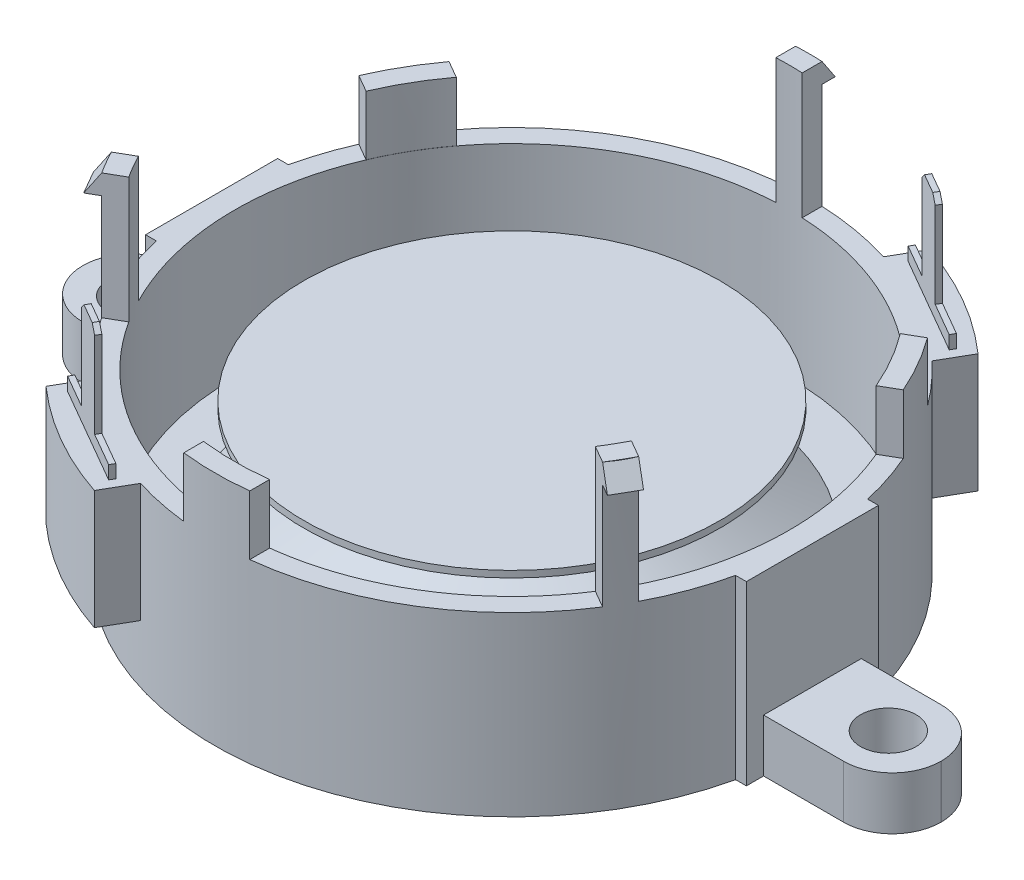
SolidWorks part; units mm, degrees
material "Полиамид ПА-6Б ТУ 6-05-988-87"
ref_plane "Спереди" through (0, 0, 0) normal (0, 0, 1) x (1, 0, 0)
ref_plane "Сверху" through (0, 0, 0) normal (0, 1, 0) x (1, 0, 0)
ref_plane "Справа" through (0, 0, 0) normal (1, 0, 0) x (0, 0, -1)
sketch "Эскиз1" plane through (0, 0, 0) normal (0, 1, 0) x (1, 0, 0)
  circle A0 centre (0, 0) radius 22.5
  dimension "D1" = 45
extrude "Бобышка-Вытянуть1" add sketch "Эскиз1" along normal blind 13.4
sketch "Эскиз2" plane through (0, 0, 0) normal (0, -1, 0) x (1, 0, 0)
  line L0 (0, 22.5) -> (0, 0) construction
  line L1 (22.1937, 3.7) -> (32.5, 3.7)
  line L3 (22.1937, -3.7) -> (32.5, -3.7)
  line L4 (32.5, 3.7) -> (32.5, -3.7)
  line L5 (-22.1937, -3.7) -> (-32.5, -3.7)
  line L7 (-22.1937, 3.7) -> (-32.5, 3.7)
  line L8 (-32.5, -3.7) -> (-32.5, 3.7)
  line L9 (32.5, 0) -> (-32.5, 0) construction
  circle A0 centre (0, 0) radius 22.5 construction
  circle A1 centre (0, 0) radius 22.5
  arc A2 (-22.1937, 3.7) -> (-22.1937, -3.7) centre (0, 0) ccw
  arc A3 (22.1937, -3.7) -> (22.1937, 3.7) centre (0, 0) ccw
  circle A4 centre (28.5, 0) radius 2.1
  circle A5 centre (-28.5, 0) radius 2.1
  dimension "D4" = 4.2
  dimension "D2" = 65
  dimension "D3" = 7.4
  dimension "D5" = 57
  dimension "D1" = 0
extrude "Бобышка-Вытянуть2" add sketch "Эскиз2" against normal blind 4
fillet "Скругление1" radius 3.69 4 edges at (32.5, 2, 3.7) (32.5, 2, -3.7) (-32.5, 2, -3.7) (-32.5, 2, 3.7)
sketch "Эскиз3" plane through (0, 13.4, 0) normal (0, 1, 0) x (1, 0, 0)
  line L0 (-1, 22.4778) -> (-1, 20.9778)
  line L2 (0, 21) -> (0, 22.5) construction
  line L3 (1, 22.4778) -> (1, 20.9778)
  line L4 (19.9663, -10.3729) -> (18.6673, -9.6229)
  line L6 (18.9663, -12.1049) -> (17.6673, -11.3549)
  line L7 (18.1865, -10.5) -> (19.4856, -11.25) construction
  line L8 (-18.9663, -12.1049) -> (-17.6673, -11.3549)
  line L10 (-19.9663, -10.3729) -> (-18.6673, -9.6229)
  line L11 (-18.1865, -10.5) -> (-19.4856, -11.25) construction
  circle A0 centre (0, 0) radius 22.5 construction
  arc A1 (1, 22.4778) -> (-1, 22.4778) centre (0, 0) ccw
  arc A2 (18.9663, -12.1049) -> (19.9663, -10.3729) centre (0, 0) ccw
  arc A3 (-19.9663, -10.3729) -> (-18.9663, -12.1049) centre (0, 0) ccw
  arc A4 (-18.6673, -9.6229) -> (-17.6673, -11.3549) centre (0, 0) ccw
  arc A5 (17.6673, -11.3549) -> (18.6673, -9.6229) centre (0, 0) ccw
  arc A6 (1, 20.9778) -> (-1, 20.9778) centre (0, 0) ccw
  point P26 (0, 0)
  dimension "D1" = 2
  dimension "D2" = 1.5
  dimension "D3" = 3
extrude "Бобышка-Вытянуть3" add sketch "Эскиз3" along normal blind 9.5
sketch "Эскиз7" plane through (-1, 0, 0) normal (-1, 0, 0) x (0, 0, 1)
  line L0 (-22.4778, 22.9) -> (-23.4778, 21.4)
  line L1 (-23.4778, 21.4) -> (-22.4778, 21.4)
  line L2 (-22.4778, 22.9) -> (-22.4778, 13.4) construction
  line L3 (-22.4778, 21.4) -> (-22.4778, 22.9)
  dimension "D1" = 1
  dimension "D2" = 1.5
extrude "Бобышка-Вытянуть5" add sketch "Эскиз7" against normal up to vertex (2 mm away) up to point (1, 22.9, -20.9778)
sketch "Эскиз4" plane through (0, 13.4, 0) normal (0, 1, 0) x (1, 0, 0)
  line L0 (-2.5, -20.8607) -> (-2.5, -22.3607)
  line L1 (0, 0) -> (0, 9.3421) construction
  line L2 (2.5, -20.8607) -> (2.5, -22.3607)
  line L3 (-16.8159, 12.5954) -> (-18.1149, 13.3454)
  line L4 (9.4761, 0) -> (0, 0) construction
  line L5 (-19.3159, 8.2653) -> (-20.6149, 9.0153)
  line L6 (19.3159, 8.2653) -> (20.6149, 9.0153)
  line L7 (16.8159, 12.5954) -> (18.1149, 13.3454)
  arc A0 (-2.5, -22.3607) -> (2.5, -22.3607) centre (0, 0) ccw
  arc A1 (-2.5, -20.8607) -> (2.5, -20.8607) centre (0, 0) ccw
  circle A2 centre (0, 0) radius 22.5 construction
  arc A3 (-18.1149, 13.3454) -> (-20.6149, 9.0153) centre (0, 0) ccw
  arc A4 (-16.8159, 12.5954) -> (-19.3159, 8.2653) centre (0, 0) ccw
  arc A5 (20.6149, 9.0153) -> (18.1149, 13.3454) centre (0, 0) ccw
  arc A6 (19.3159, 8.2653) -> (16.8159, 12.5954) centre (0, 0) ccw
  point P22 (0, 0)
  dimension "D1" = 5
  dimension "D2" = 1.5
  dimension "D3" = 3
extrude "Бобышка-Вытянуть4" add sketch "Эскиз4" along normal blind 4.5
sketch "Эскиз5" plane through (0, 13.4, 0) normal (0, 1, 0) x (1, 0, 0)
  circle A0 centre (0, 0) radius 21.0016
  dimension "D1" = 42.0032
extrude "Вырез-Вытянуть1" cut sketch "Эскиз5" against normal blind 11
sketch "Эскиз6" plane through (0, 0, 0) normal (0, -1, 0) x (-1, 0, 0)
  circle A0 centre (0, 0) radius 8
  dimension "D1" = 16
extrude "Вырез-Вытянуть2" cut sketch "Эскиз6" against normal blind 3
pattern_circular "Круговой массив1" count 3 over 360 about axis through (0, 0, 0) along (0, 1, 0) of "Бобышка-Вытянуть5"
sketch "Эскиз8" plane through (0, 13.4, 0) normal (0, 1, 0) x (1, 0, 0)
  line L0 (7.9173, 23.7132) -> (6.6386, 21.4984)
  line L1 (0, 0) -> (13.8032, 23.9079) construction
  line L2 (16.5776, 18.7132) -> (15.2988, 16.4984)
  line L3 (0, 14.8355) -> (0, 0) construction
  line L4 (14.3383, 0) -> (0, 0) construction
  line L5 (-7.9173, -23.7132) -> (-6.6386, -21.4984)
  line L6 (-16.5776, -18.7132) -> (-15.2988, -16.4984)
  circle A0 centre (0, 0) radius 22.5 construction
  arc A1 (-15.2988, -16.4984) -> (-6.6386, -21.4984) centre (0, 0) ccw
  arc A2 (-16.5776, -18.7132) -> (-7.9173, -23.7132) centre (0, 0) ccw
  arc A3 (15.2988, 16.4984) -> (6.6386, 21.4984) centre (0, 0) ccw
  arc A4 (16.5776, 18.7132) -> (7.9173, 23.7132) centre (0, 0) ccw
  point P20 (0, 0)
  dimension "D1" = 50
  dimension "D2" = 10
  dimension "D3" = 30
  dimension "D4" = 2
extrude "Бобышка-Вытянуть6" add sketch "Эскиз8" against normal blind 9
sketch "Эскиз9" plane through (0, 13.4, 0) normal (0, 1, 0) x (1, 0, 0)
  line L0 (8.0694, 22.4766) -> (7.8694, 22.1302)
  line L1 (7.8694, 22.1302) -> (15.2306, 17.8802)
  line L2 (15.2306, 17.8802) -> (15.4306, 18.2266)
  line L3 (15.4306, 18.2266) -> (8.0694, 22.4766)
  line L4 (0, 0) -> (12.5, 21.6506) construction
  line L5 (7.9173, 23.7132) -> (6.6386, 21.4984) construction
  line L6 (0, 0) -> (11.2177, -6.4765) construction
  line L7 (-8.0694, -22.4766) -> (-15.4306, -18.2266)
  line L8 (-7.8694, -22.1302) -> (-8.0694, -22.4766)
  line L9 (-15.2306, -17.8802) -> (-7.8694, -22.1302)
  line L10 (-15.4306, -18.2266) -> (-15.2306, -17.8802)
  arc A0 (16.5776, 18.7132) -> (7.9173, 23.7132) centre (0, 0) ccw construction
  dimension "D1" = 8.5
  dimension "D2" = 0.4
  dimension "D3" = 47
extrude "Бобышка-Вытянуть7" add sketch "Эскиз9" along normal blind 1
sketch "Эскиз10" plane through (0, 14.4, 0) normal (0, 1, 0) x (1, 0, 0)
  line L0 (10.5809, 21.0266) -> (10.3809, 20.6802)
  line L1 (15.4306, 18.2266) -> (8.0694, 22.4766) construction
  line L2 (7.8694, 22.1302) -> (15.2306, 17.8802) construction
  line L3 (10.3809, 20.6802) -> (12.7191, 19.3302)
  line L4 (12.7191, 19.3302) -> (12.9191, 19.6766)
  line L5 (12.9191, 19.6766) -> (10.5809, 21.0266)
  line L6 (0, 0) -> (12.5, 21.6506) construction
  line L7 (0, 0) -> (11.9851, -6.9196) construction
  line L8 (-10.5809, -21.0266) -> (-12.9191, -19.6766)
  line L9 (-10.3809, -20.6802) -> (-10.5809, -21.0266)
  line L10 (-12.7191, -19.3302) -> (-10.3809, -20.6802)
  line L11 (-12.9191, -19.6766) -> (-12.7191, -19.3302)
  arc A0 (16.5776, 18.7132) -> (7.9173, 23.7132) centre (0, 0) ccw construction
  dimension "D1" = 2.7
extrude "Бобышка-Вытянуть8" add sketch "Эскиз10" along normal blind 7
chamfer "Фаска1" distance 0.5 angle 45 4 edges at (10.4809, 21.4, -20.8534) (12.8191, 21.4, -19.5034) (-12.8191, 21.4, 19.5034) (-10.4809, 21.4, 20.8534)
sketch "Эскиз11" plane through (0, 0, 0) normal (1, 0, 0) x (0, 0, -1)
  line L0 (-0.01, 0) -> (-0.01, 22.8012) construction
  line L1 (20.5, 2.4) -> (17.5, 2.4)
  line L2 (17.5, 2.4) -> (4.99, 9.6227)
  line L3 (4.99, 9.6227) -> (4.99, 10.9)
  line L4 (4.99, 10.9) -> (15.74, 10.9)
  line L5 (15.74, 10.9) -> (15.74, 11.4)
  line L6 (15.74, 11.4) -> (-0.01, 11.4)
  line L7 (8, 2.4) -> (-8, 2.4) construction
  line L8 (20.5, 2.4) -> (20.5, 1.9)
  line L9 (20.5, 1.9) -> (17.366, 1.9)
  line L10 (17.366, 1.9) -> (4.49, 9.334)
  line L11 (4.49, 9.334) -> (4.49, 10.9)
  line L12 (4.49, 10.9) -> (-0.01, 10.9)
  line L13 (-0.01, 10.9) -> (-0.01, 11.4)
  line L15 (16.4984, 13.4) -> (13.3454, 13.4) construction
  line L16 (22.5, 0) -> (22.5, 21.4) construction
  dimension "D1" = 0.5
  dimension "D2" = 0.5
  dimension "D3" = 3
  dimension "D4" = 2
  dimension "D5" = 0.5
  dimension "D6" = 0.5
  dimension "D7" = 2
  dimension "D8" = 150
  dimension "D9" = 5
  dimension "D10" = 31.5
revolve "Повернуть1" add sketch "Эскиз11" angle 360 about L0
sketch "Эскиз12" plane through (0, 4, 0) normal (0, 1, 0) x (1, 0, 0)
  circle A0 centre (0, 0) radius 22.5
  circle A1 centre (0, 0) radius 34
  arc A2 (6.6386, 21.4984) -> (1, 22.4778) centre (0, 0) ccw construction
  dimension "D1" = 68
extrude "Вырез-Вытянуть3" [suppressed] cut sketch "Эскиз12" against normal up to vertex
sketch "Эскиз13" plane through (0, 0, 0) normal (0, -1, 0) x (1, 0, 0)
  circle A0 centre (0, 0) radius 9.5
  dimension "D1" = 19
extrude "Вырез-Вытянуть4" cut sketch "Эскиз13" against normal blind 2
sketch "Эскиз15" plane through (0, 0, 0) normal (0, -1, 0) x (1, 0, 0)
  line L0 (0, 0) -> (-13.2112, 0) construction
  line L1 (-21.9374, 5) -> (-22.75, 5)
  line L2 (-21.9374, -5) -> (-22.75, -5)
  line L3 (-22.75, 5) -> (-22.75, -5)
  line L4 (0, 0) -> (0, 11.1502) construction
  line L5 (22.75, 5) -> (22.75, -5)
  line L6 (21.9374, -5) -> (22.75, -5)
  line L7 (21.9374, 5) -> (22.75, 5)
  arc A0 (22.1937, 3.7) -> (-22.1937, 3.7) centre (0, 0) ccw construction
  arc A1 (-21.9374, -5) -> (-21.9374, 5) centre (0, 0) cw
  arc A2 (21.9374, -5) -> (21.9374, 5) centre (0, 0) ccw
  dimension "D2" = 45.5
  dimension "D1" = 10
extrude "Бобышка-Вытянуть10" add sketch "Эскиз15" against normal up to surface (13.4 mm away) up to face at (-15.9013, 13.4, -9.1806)
